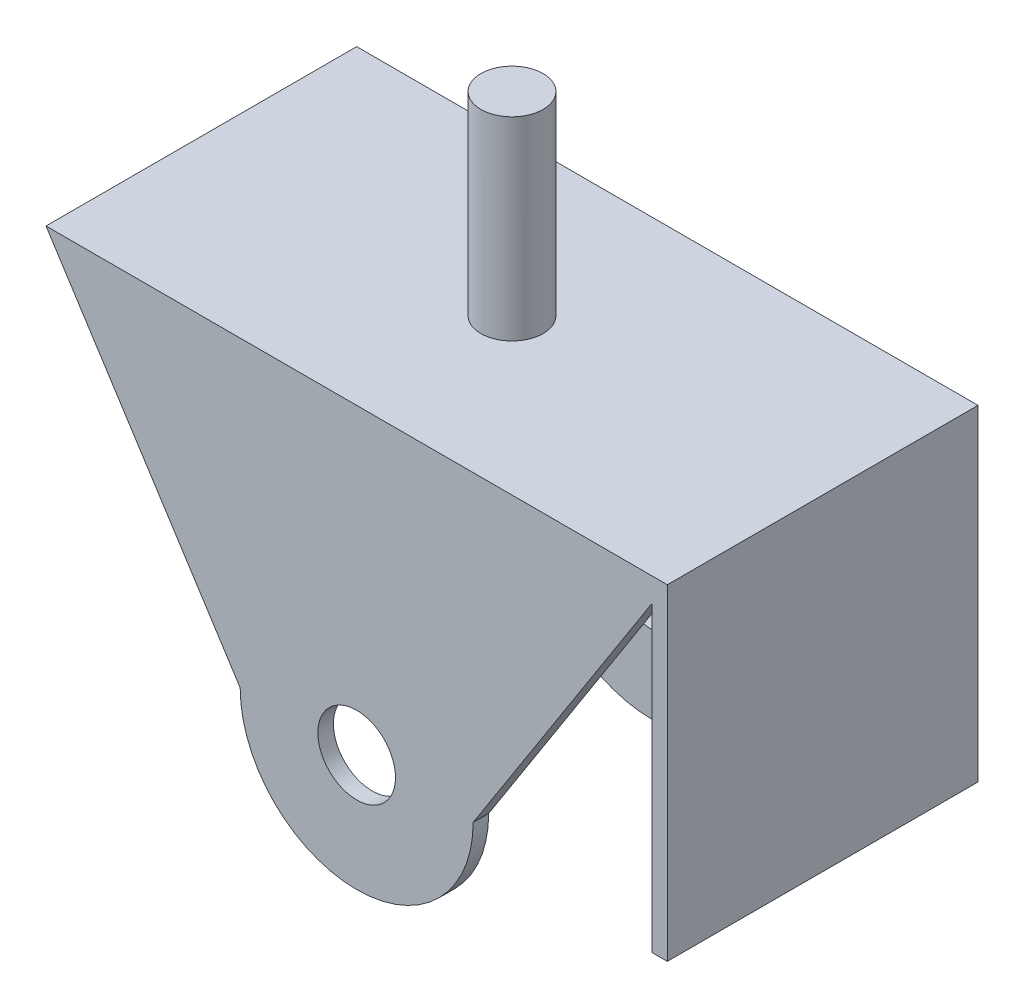
SolidWorks part; units mm, degrees
ref_plane "前视基准面" through (0, 0, 0) normal (0, 0, 1) x (1, 0, 0)
ref_plane "上视基准面" through (0, 0, 0) normal (0, 1, 0) x (1, 0, 0)
ref_plane "右视基准面" through (0, 0, 0) normal (1, 0, 0) x (0, 0, -1)
sketch "草图1" plane through (0, 0, 0) normal (0, 0, 1) x (1, 0, 0)
  line L0 (0, 0) -> (0, 39) construction
  line L1 (0, 39) -> (-40, 39)
  line L2 (0, 39) -> (40, 39)
  line L3 (-40, 39) -> (-15, 0)
  line L4 (15, 0) -> (40, 39)
  circle A0 centre (0, 0) radius 25 construction
  circle A1 centre (0, 0) radius 5
  circle A2 centre (0, 0) radius 15 construction
  arc A3 (-15, 0) -> (15, 0) centre (0, 0) ccw
  dimension "D1" = 50
  dimension "D3" = 10
  dimension "D2" = 39
extrude "凸台-拉伸1" add sketch "草图1" along normal blind 40
ref_plane "基准面1" through (0, 0, 20) normal (0, 0, 1) x (1, 0, 0)
sketch "草图2" plane through (0, 0, 20) normal (0, 0, 1) x (1, 0, 0)
  line L0 (0, 0) -> (0, 64.6211) construction
  line L3 (40.6474, -37) -> (-40.6474, -37)
  line L4 (40.6474, -37) -> (40.6474, 37)
  line L5 (40.6474, 37) -> (-40.6474, 37)
  line L6 (-40.6474, -37) -> (-40.6474, 37)
  line L7 (40.6474, -37) -> (-40.6474, 37) construction
  line L8 (40.6474, 37) -> (-40.6474, -37) construction
  line L9 (40, 39) -> (-40, 39) construction
  dimension "D1" = 2
extrude "切除-拉伸1" cut sketch "草图2" against normal blind 18 and the other way blind 18
sketch "草图3" plane through (0, 39, 0) normal (0, 1, 0) x (1, 0, 0)
  line L0 (-40, 0) -> (40, -40) construction
  circle A0 centre (0, -20) radius 4
  dimension "D1" = 8
extrude "凸台-拉伸2" add sketch "草图3" along normal blind 25
sketch "草图4" plane through (0, 39, 0) normal (0, 1, 0) x (1, 0, 0)
  line L0 (40, -40) -> (-40, -40) construction
  line L1 (40, 0) -> (38, 0)
  line L2 (40, 0) -> (40, -40)
  line L3 (40, -40) -> (38, -40)
  line L4 (38, 0) -> (38, -40)
  dimension "D1" = 2
extrude "凸台-拉伸3" add sketch "草图4" against normal blind 42
